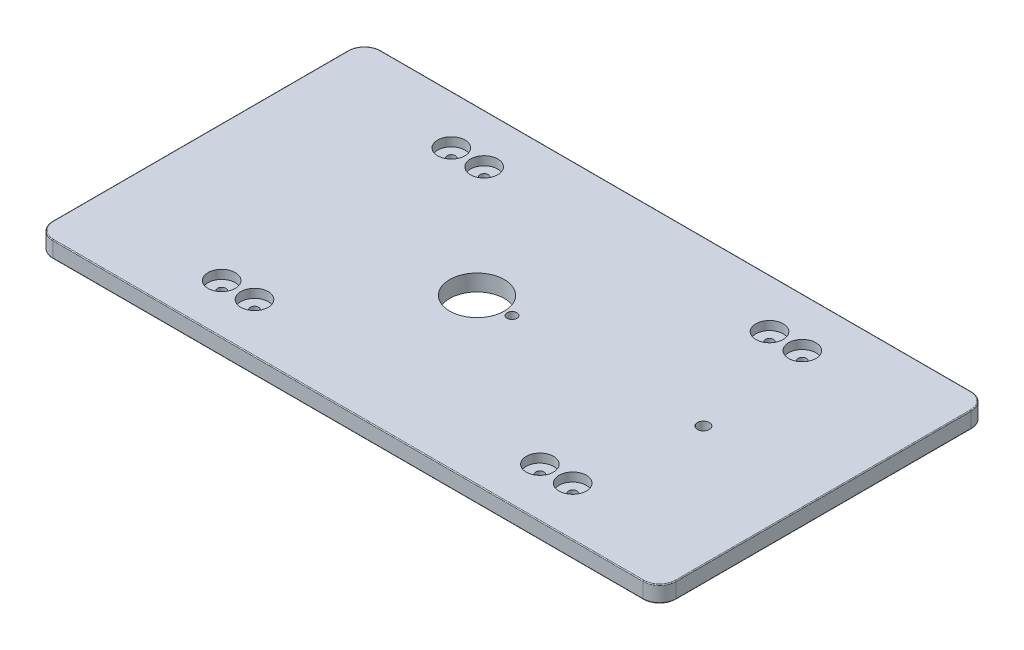
SolidWorks part; units mm, degrees
ref_plane "Front Plane" through (0, 0, 0) normal (0, 0, 1) x (1, 0, 0)
ref_plane "Top Plane" through (0, 0, 0) normal (0, 1, 0) x (1, 0, 0)
ref_plane "Right Plane" through (0, 0, 0) normal (1, 0, 0) x (0, 0, -1)
sketch "Sketch2" plane through (0, 0, 0) normal (0, 1, 0) x (1, 0, 0)
  line L1 (-285, -150) -> (285, -150)
  line L2 (-285, -150) -> (-285, 150)
  line L3 (-285, 150) -> (285, 150)
  line L4 (285, -150) -> (285, 150)
  line L5 (-285, -150) -> (285, 150) construction
  line L6 (-285, 150) -> (285, -150) construction
  line L13 (0, 0) -> (0, 150) construction
  line L14 (0, 0) -> (285, 0) construction
  circle A5 centre (-160.5, -105) radius 3.75
  circle A6 centre (-130.5, -105) radius 3.75
  circle A7 centre (-130.5, 105) radius 3.75
  circle A8 centre (-160.5, 105) radius 3.75
  circle A9 centre (160.5, 105) radius 3.75
  circle A10 centre (130.5, 105) radius 3.75
  circle A11 centre (160.5, -105) radius 3.75
  circle A12 centre (130.5, -105) radius 3.75
  point P0 (0, 0)
  point P5 (0, 0)
  dimension "D8" = 30
  dimension "D9" = 45
  dimension "D3" = 7.5
  dimension "D1" = 300
  dimension "D2" = 570
  dimension "D10" = 130.5
extrude "Boss-Extrude1" add sketch "Sketch2" along normal blind 15
fillet "Fillet1" radius 15 4 edges at (-285, 7.5, 150) (-285, 7.5, -150) (285, 7.5, -150) (285, 7.5, 150)
fillet "Fillet2" radius 0.75 32 edges at (130.5, 0, 101.25) (130.5, 15, 101.25) (160.5, 0, 101.25) (160.5, 15, 101.25) (130.5, 0, -101.25) (130.5, 15, -101.25) (160.5, 0, -101.25) (160.5, 15, -101.25) (-160.5, 0, -108.75) (-160.5, 15, -108.75) (-130.5, 0, -108.75) (-130.5, 15, -108.75) (-130.5, 0, 108.75) (-130.5, 15, 108.75) (-160.5, 0, 108.75) (-160.5, 15, 108.75) (285, 0, 0) (0, 0, -150) (-285, 0, 0) (0, 0, 150) (285, 15, 0) (0, 15, -150) (-285, 15, 0) (280.6066, 0, 145.6066) (280.6066, 0, -145.6066) (-280.6066, 0, -145.6066) (-280.6066, 0, 145.6066) (280.6066, 15, 145.6066) (280.6066, 15, -145.6066) (-280.6066, 15, -145.6066) (-280.6066, 15, 145.6066) (0, 15, 150)
sketch "Sketch3" plane through (0, 15, 0) normal (0, 1, 0) x (1, 0, 0)
  circle A0 centre (175, 0) radius 5.5
  dimension "D1" = 11
  dimension "D2" = 175
extrude "Cut-Extrude1" cut sketch "Sketch3" against normal through all
sketch "Sketch4" plane through (0, 15, 0) normal (0, 1, 0) x (1, 0, 0)
  circle A0 centre (0, 0) radius 4.5
  dimension "D1" = 9
extrude "Cut-Extrude2" cut sketch "Sketch4" against normal up to next
sketch "Sketch5" plane through (0, 15, 0) normal (0, 1, 0) x (1, 0, 0)
  circle A0 centre (-32, 0) radius 25
  dimension "D1" = 50
  dimension "D2" = 32
extrude "Cut-Extrude3" cut sketch "Sketch5" against normal through all
sketch "Sketch6" plane through (0, 15, 0) normal (0, 1, 0) x (1, 0, 0)
  circle A0 centre (160.5, 105) radius 12.5
  circle A1 centre (130.5, 105) radius 12.5
  circle A3 centre (-130.5, 105) radius 12.5
  circle A5 centre (-160.5, 105) radius 12.5
  circle A10 centre (-160.5, -105) radius 12.5
  circle A12 centre (130.5, 105) radius 4.5 construction
  circle A14 centre (-130.5, 105) radius 4.5 construction
  circle A15 centre (-160.5, 105) radius 4.5 construction
  circle A17 centre (-160.5, -105) radius 3.75 construction
  circle A18 centre (-130.5, -105) radius 12.5
  circle A21 centre (130.5, -105) radius 12.5
  circle A23 centre (160.5, -105) radius 12.5
  circle A27 centre (130.5, -105) radius 4.5 construction
  circle A28 centre (160.5, -105) radius 3.75 construction
  dimension "D1" = 25
extrude "Cut-Extrude4" cut sketch "Sketch6" against normal blind 8
scale "Scale1" scale about centroid uniform scaling yes scale factor 0.5
